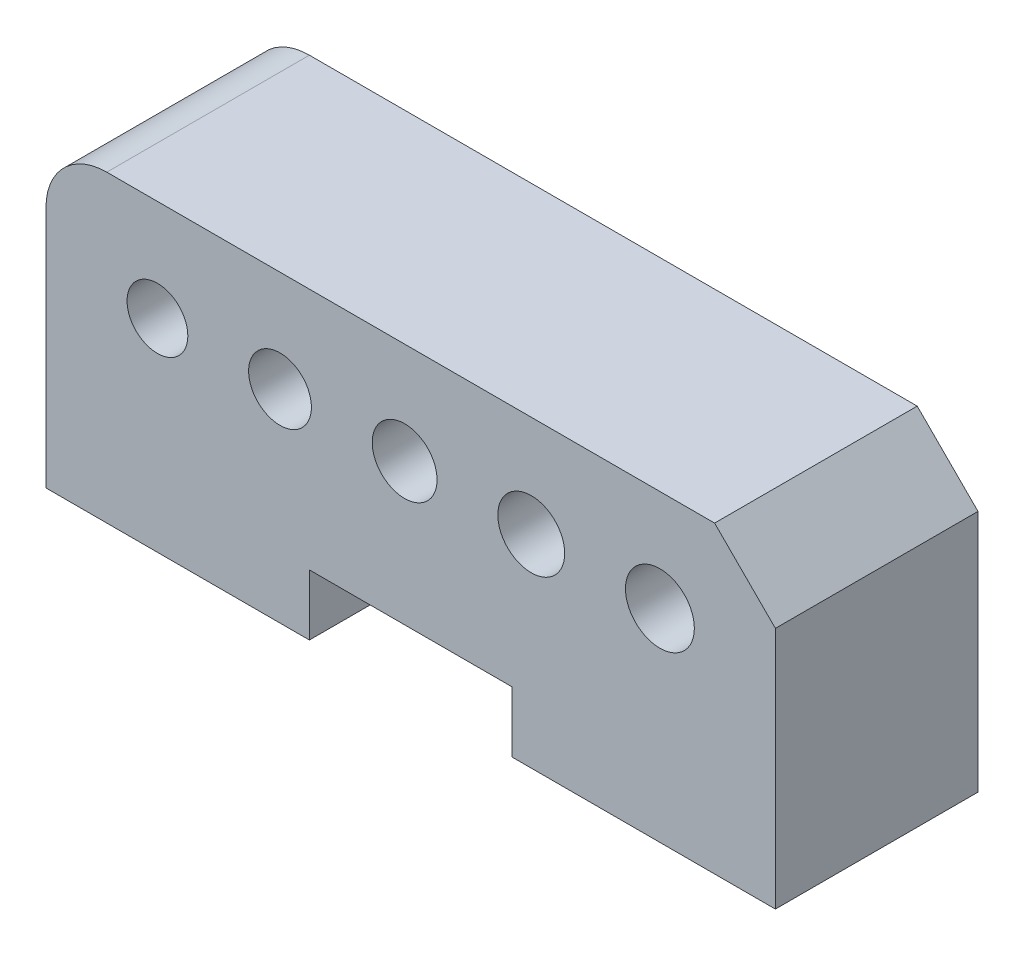
SolidWorks part; units mm, degrees
ref_plane "Front Plane" through (0, 0, 0) normal (0, 0, 1) x (1, 0, 0)
ref_plane "Top Plane" through (0, 0, 0) normal (0, 1, 0) x (1, 0, 0)
ref_plane "Right Plane" through (0, 0, 0) normal (1, 0, 0) x (0, 0, -1)
sketch "Sketch1" plane through (0, 0, 0) normal (0, 0, 1) x (1, 0, 0)
  line L0 (-18, 0) -> (45.3877, 0) construction
  line L1 (-14, 0) -> (-14, -5) construction
  line L2 (-18, -5) -> (-18, 5) construction
  line L3 (-18, 5) -> (18, 5) construction
  line L4 (18, -5) -> (18, 5) construction
  line L5 (-18, -5) -> (18, 5) construction
  line L6 (-18, 5) -> (18, -5) construction
  line L7 (-14, -5) -> (13.3812, -5) construction
  line L8 (13.3812, -5) -> (14, 0) construction
  line L10 (18, 5) -> (-18, 5)
  line L11 (18, 5) -> (18, -10)
  line L12 (18, -10) -> (-18, -10)
  line L13 (-18, 5) -> (-18, -10)
  circle A0 centre (-6.45, 0) radius 1.55
  circle A1 centre (-12.5, 0) radius 1.5
  circle A2 centre (-0.3, 0) radius 1.6
  circle A3 centre (5.95, 0) radius 1.65
  circle A4 centre (12.3, 0) radius 1.7
  point P0 (0, 0)
  dimension "D3" = 4
  dimension "D2" = 4
  dimension "D4" = 3
  dimension "D5" = 3
  dimension "D6" = 3
  dimension "D7" = 3
  dimension "D8" = 3
  dimension "D9" = 3.1
  dimension "D10" = 3.2
  dimension "D11" = 3.3
  dimension "D12" = 3.4
  dimension "D1" = 10
  dimension "D13" = 5
extrude "Boss-Extrude1" add sketch "Sketch1" along normal blind 10 contours L10 L13 L12 L11 A4 A3 A2 A1 A0
sketch "Sketch2" plane through (0, 0, 10) normal (0, 0, 1) x (1, 0, 0)
  line L4 (18, 5) -> (-18, 5)
  line L5 (18, -10) -> (18, 5)
  line L6 (-18, -10) -> (18, -10)
  line L7 (-18, 5) -> (-18, -10)
  line L8 (18, 5) -> (-18, 5)
  line L9 (18, -10) -> (18, 5)
  line L10 (-18, -10) -> (18, -10)
  line L11 (-18, 5) -> (-18, -10)
  circle A1 centre (5.95, 0) radius 1.65
  circle A2 centre (5.95, 0) radius 1.65
  circle A3 centre (-0.3, 0) radius 1.6
  circle A4 centre (-0.3, 0) radius 1.6
  circle A5 centre (-12.5, 0) radius 1.5
  circle A6 centre (-12.5, 0) radius 1.5
  circle A7 centre (-6.45, 0) radius 1.55
  circle A8 centre (-6.45, 0) radius 1.55
  circle A9 centre (12.3, 0) radius 1.7
  circle A10 centre (12.3, 0) radius 1.7
  dimension "D1" = 0
  dimension "D2" = 0
  dimension "D3" = 0
  dimension "D4" = 0
  dimension "D5" = 0
  dimension "D6" = 0
fillet "Fillet2" radius 3 1 edges at (-18, 5, 5)
chamfer "Chamfer2" distance 3 angle 45 1 edges at (18, 5, 5)
sketch "Sketch3" plane through (0, 0, 10) normal (0, 0, 1) x (1, 0, 0)
  line L0 (-18, -10) -> (18, -10) construction
  line L1 (-5, -13) -> (5, -13)
  line L2 (-5, -13) -> (-5, -7)
  line L3 (-5, -7) -> (5, -7)
  line L4 (5, -13) -> (5, -7)
  line L5 (-5, -13) -> (5, -7) construction
  line L6 (-5, -7) -> (5, -13) construction
  point P0 (0, -10)
  dimension "D1" = 10
  dimension "D2" = 6
extrude "Cut-Extrude1" cut sketch "Sketch3" against normal blind 10
